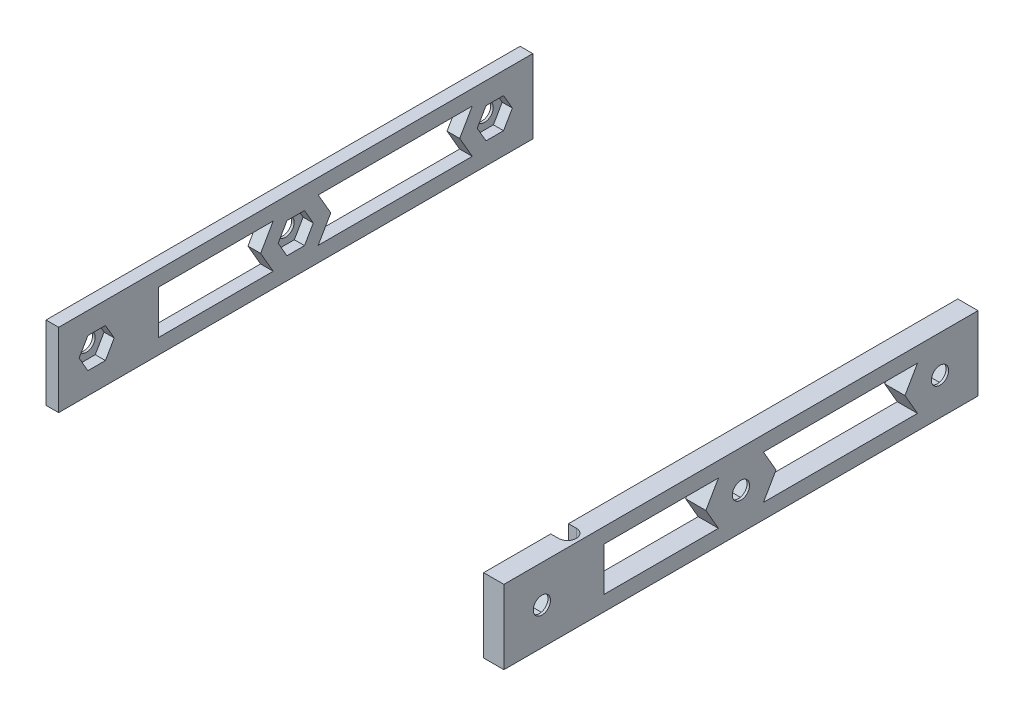
SolidWorks part; units mm, degrees
ref_plane "Front Plane" through (0, 0, 0) normal (0, 0, 1) x (1, 0, 0)
ref_plane "Top Plane" through (0, 0, 0) normal (0, 1, 0) x (1, 0, 0)
ref_plane "Right Plane" through (0, 0, 0) normal (1, 0, 0) x (0, 0, -1)
sketch "Sketch1" plane through (0, 0, 0) normal (0, 1, 0) x (1, 0, 0)
  line L1 (-45.2, -46.8) -> (45.2, -46.8)
  line L2 (-45.2, -46.8) -> (-45.2, 46.8)
  line L3 (-45.2, 46.8) -> (45.2, 46.8)
  line L4 (45.2, -46.8) -> (45.2, 46.8)
  line L5 (-45.2, -46.8) -> (45.2, 46.8) construction
  line L6 (-45.2, 46.8) -> (45.2, -46.8) construction
  line L7 (-45.2, -46.8) -> (-42.7, -46.8)
  line L8 (-45.2, -46.8) -> (-45.2, 46.8)
  line L9 (-45.2, 46.8) -> (-42.7, 46.8)
  line L10 (-42.7, -46.8) -> (-42.7, 46.8)
  line L11 (-45.2, -46.8) -> (-42.7, 46.8) construction
  line L12 (-45.2, 46.8) -> (-42.7, -46.8) construction
  line L13 (45.2, -46.8) -> (41.2, -46.8)
  line L14 (45.2, -46.8) -> (45.2, 46.8)
  line L15 (45.2, 46.8) -> (41.2, 46.8)
  line L16 (41.2, -46.8) -> (41.2, 46.8)
  line L17 (45.2, -46.8) -> (41.2, 46.8) construction
  line L18 (45.2, 46.8) -> (41.2, -46.8) construction
  point P0 (0, 0)
  point P6 (-43.95, 0)
  point P11 (43.2, 0)
  dimension "D1" = 93.6
  dimension "D2" = 90.4
  dimension "D3" = 2.5
  dimension "D4" = 4
extrude "Boss-Extrude1" add sketch "Sketch1" along normal blind 14.6 contours L1 L10 L3 L2 | L16 L1 L4 L3
sketch "Sketch4" plane through (0, 14.6, 0) normal (0, 1, 0) x (1, 0, 0)
  line L0 (41.2, -46.8) -> (45.2, -46.8) construction
  line L1 (45.2, -46.8) -> (45.2, 46.8) construction
  line L2 (42.75, -31.8) -> (42.75, -30.05)
  line L3 (42.75, -30.05) -> (41.2, -30.05)
  line L4 (41.2, -46.8) -> (41.2, 46.8) construction
  line L5 (42.75, -31.8) -> (42.75, -33.55)
  line L6 (42.75, -33.55) -> (41.2, -33.55)
  line L7 (41.2, -33.55) -> (41.2, -30.05)
  circle A0 centre (42.75, -31.8) radius 1.75
  line M2 (41.2, 46.8) -> (41.2, -46.8)
  dimension "D3" = 3.5
  dimension "D1" = 15
  dimension "D2" = 2.45
extrude "Cut-Extrude1" cut sketch "Sketch4" against normal through all contours L5 A0 L2 | L2 A0 L7 L5 | A0 L6 M2 | A0 L3 M2
hole_wizard "M3 Clearance Hole1" positions "Sketch6" profile "Sketch7" hole size "M3" standard "ANSI Metric" end condition through all
sketch "Sketch6" plane through (45.2, 0, 0) normal (1, 0, 0) x (0, 0, -1)
  line L0 (-46.8, 7.3) -> (46.8, 7.3)
  line L1 (-46.8, 14.6) -> (-46.8, 0) construction
  line L2 (46.8, 14.6) -> (46.8, 0) construction
  point P8 (-39.3, 7.3)
  point P10 (39.3, 7.3)
  point P12 (0, 7.3)
  dimension "D1" = 7.5
  dimension "D2" = 7.5
sketch "Sketch7" plane through (45.2, 7.3, 0) normal (0, 1, 0) x (0, 0, -1)
  line L0 (0, 0) -> (0, 90.4)
  line L1 (0, 90.4) -> (1.7, 90.4)
  line L2 (1.7, 90.4) -> (1.7, 0)
  line L5 (1.7, 0) -> (0, 0)
  line L11 (0, -6.35) -> (0, 107.95) construction
  dimension "Thru Hole Dia." = 3.4
  dimension "Thru Hole Depth" = 90.4
sketch "Sketch8" plane through (41.2, 0, 0) normal (-1, 0, 0) x (0, 0, 1)
  line L1 (-35.8359, 7.3) -> (-37.5679, 10.3)
  line L2 (-37.5679, 10.3) -> (-41.0321, 10.3)
  line L3 (-41.0321, 10.3) -> (-42.7641, 7.3)
  line L4 (-42.7641, 7.3) -> (-41.0321, 4.3)
  line L5 (-41.0321, 4.3) -> (-37.5679, 4.3)
  line L6 (-37.5679, 4.3) -> (-35.8359, 7.3)
  line L7 (3.4641, 7.3) -> (1.7321, 10.3)
  line L8 (1.7321, 10.3) -> (-1.7321, 10.3)
  line L9 (-1.7321, 10.3) -> (-3.4641, 7.3)
  line L10 (-3.4641, 7.3) -> (-1.7321, 4.3)
  line L11 (-1.7321, 4.3) -> (1.7321, 4.3)
  line L12 (1.7321, 4.3) -> (3.4641, 7.3)
  line L13 (42.7641, 7.3) -> (41.0321, 10.3)
  line L14 (41.0321, 10.3) -> (37.5679, 10.3)
  line L15 (37.5679, 10.3) -> (35.8359, 7.3)
  line L16 (35.8359, 7.3) -> (37.5679, 4.3)
  line L17 (37.5679, 4.3) -> (41.0321, 4.3)
  line L18 (41.0321, 4.3) -> (42.7641, 7.3)
  circle A0 centre (-39.3, 7.3) radius 3.4641 construction
  circle A1 centre (0, 7.3) radius 3.4641 construction
  circle A2 centre (39.3, 7.3) radius 3 construction
  dimension "D1" = 3
extrude "Cut-Extrude2" cut sketch "Sketch8" against normal blind 3.5
mirror "Mirror1" about plane through (0, 0, 0) normal (1, 0, 0) of "Cut-Extrude2"
sketch "Sketch10" [suppressed] plane through (0, 14.6, 0) normal (0, 1, 0) x (1, 0, 0)
  line L0 (42.75, -33.55) -> (41.2, -33.55) construction
  line L1 (41.2, -33.55) -> (41.2, -46.8) construction
  line L2 (41.2, -46.8) -> (45.2, -46.8) construction
  line L3 (45.2, -46.8) -> (45.2, 46.8) construction
  line L4 (45.2, 46.8) -> (41.2, 46.8) construction
  line L5 (41.2, 46.8) -> (41.2, -30.05) construction
  line L6 (41.2, -30.05) -> (42.75, -30.05) construction
  line L7 (-45.2, -46.8) -> (-42.7, -46.8) construction
  line L8 (-42.7, -46.8) -> (-42.7, 46.8) construction
  line L9 (-42.7, 46.8) -> (-45.2, 46.8) construction
  line L10 (-45.2, 46.8) -> (-45.2, -46.8) construction
  line L11 (42.75, -33.55) -> (41.2, -33.55)
  line L12 (41.2, -33.55) -> (41.2, -46.8)
  line L13 (41.2, -46.8) -> (45.2, -46.8)
  line L14 (45.2, -46.8) -> (45.2, 46.8)
  line L15 (45.2, 46.8) -> (41.2, 46.8)
  line L16 (41.2, 46.8) -> (41.2, -30.05)
  line L17 (41.2, -30.05) -> (42.75, -30.05)
  line L18 (-45.2, -46.8) -> (-42.7, -46.8)
  line L19 (-42.7, -46.8) -> (-42.7, 46.8)
  line L20 (-42.7, 46.8) -> (-45.2, 46.8)
  line L21 (-45.2, 46.8) -> (-45.2, -46.8)
  arc A0 (42.75, -33.55) -> (42.75, -30.05) centre (42.75, -31.8) ccw construction
  arc A1 (42.75, -33.55) -> (42.75, -30.05) centre (42.75, -31.8) ccw
extrude "Boss-Extrude2" [suppressed] add sketch "Sketch10" along normal blind 7.5
sketch "Sketch11" [suppressed] plane through (0, 0, 0) normal (0, -1, 0) x (1, 0, 0)
  line L0 (-42.7, 46.8) -> (-45.2, 46.8) construction
  line L1 (-45.2, 46.8) -> (-45.2, -46.8) construction
  line L2 (-45.2, -46.8) -> (-42.7, -46.8) construction
  line L3 (-42.7, -46.8) -> (-42.7, 46.8) construction
  line L4 (41.2, 33.55) -> (42.75, 33.55) construction
  line L5 (42.75, 30.05) -> (41.2, 30.05) construction
  line L6 (41.2, 30.05) -> (41.2, -46.8) construction
  line L7 (41.2, -46.8) -> (45.2, -46.8) construction
  line L8 (45.2, -46.8) -> (45.2, 46.8) construction
  line L9 (45.2, 46.8) -> (41.2, 46.8) construction
  line L10 (41.2, 46.8) -> (41.2, 33.55) construction
  line L11 (-42.7, 46.8) -> (-45.2, 46.8)
  line L12 (-45.2, 46.8) -> (-45.2, -46.8)
  line L13 (-45.2, -46.8) -> (-42.7, -46.8)
  line L14 (-42.7, -46.8) -> (-42.7, 46.8)
  line L15 (41.2, 33.55) -> (42.75, 33.55)
  line L16 (42.75, 30.05) -> (41.2, 30.05)
  line L17 (41.2, 30.05) -> (41.2, -46.8)
  line L18 (41.2, -46.8) -> (45.2, -46.8)
  line L19 (45.2, -46.8) -> (45.2, 46.8)
  line L20 (45.2, 46.8) -> (41.2, 46.8)
  line L21 (41.2, 46.8) -> (41.2, 33.55)
  arc A0 (42.75, 30.05) -> (42.75, 33.55) centre (42.75, 31.8) ccw construction
  arc A1 (42.75, 30.05) -> (42.75, 33.55) centre (42.75, 31.8) ccw
extrude "Boss-Extrude3" [suppressed] add sketch "Sketch11" along normal blind 7.5
sketch "Sketch12" [suppressed] plane through (41.2, 0, 0) normal (-1, 0, 0) x (0, 0, 1)
  line L0 (-32.3718, 7.3) -> (-35.8359, 1.3)
  line L1 (-35.8359, 1.3) -> (-42.7641, 1.3)
  line L2 (-42.7641, 1.3) -> (-46.2282, 7.3)
  line L3 (-46.2282, 7.3) -> (-42.7641, 13.3)
  line L4 (-42.7641, 13.3) -> (-35.8359, 13.3)
  line L5 (-35.8359, 13.3) -> (-32.3718, 7.3)
  line L7 (3.4641, 13.3) -> (6.9282, 7.3)
  line L8 (-35.8359, 7.3) -> (-37.5679, 4.3) construction
  line L9 (-37.5679, 4.3) -> (-41.0321, 4.3) construction
  line L10 (-41.0321, 4.3) -> (-42.7641, 7.3) construction
  line L11 (-42.7641, 7.3) -> (-41.0321, 10.3) construction
  line L12 (28.05, -5.5) -> (28.05, 20.1)
  line L13 (28.05, 20.1) -> (-44.8, 20.1)
  line L14 (-44.8, 20.1) -> (-44.8, -5.5)
  line L15 (-44.8, -5.5) -> (28.05, -5.5)
  line L16 (28.05, -5.5) -> (28.05, 20.1)
  line L17 (28.05, 20.1) -> (-44.8, 20.1)
  line L18 (-44.8, 20.1) -> (-44.8, -5.5)
  line L19 (-44.8, -5.5) -> (28.05, -5.5)
  line L20 (-41.0321, 10.3) -> (-37.5679, 10.3) construction
  line L21 (-37.5679, 10.3) -> (-35.8359, 7.3) construction
  line L22 (3.4641, 7.3) -> (1.7321, 4.3) construction
  line L23 (1.7321, 4.3) -> (-1.7321, 4.3) construction
  line L24 (-1.7321, 4.3) -> (-3.4641, 7.3) construction
  line L25 (-3.4641, 7.3) -> (-1.7321, 10.3) construction
  line L26 (-1.7321, 10.3) -> (1.7321, 10.3) construction
  line L27 (1.7321, 10.3) -> (3.4641, 7.3) construction
  line L28 (-35.8359, 7.3) -> (-37.5679, 4.3)
  line L29 (-37.5679, 4.3) -> (-41.0321, 4.3)
  line L30 (-41.0321, 4.3) -> (-42.7641, 7.3)
  line L31 (-42.7641, 7.3) -> (-41.0321, 10.3)
  line L32 (-41.0321, 10.3) -> (-37.5679, 10.3)
  line L33 (-37.5679, 10.3) -> (-35.8359, 7.3)
  line L34 (3.4641, 7.3) -> (1.7321, 4.3)
  line L35 (1.7321, 4.3) -> (-1.7321, 4.3)
  line L36 (-1.7321, 4.3) -> (-3.4641, 7.3)
  line L37 (-3.4641, 7.3) -> (-1.7321, 10.3)
  line L38 (-1.7321, 10.3) -> (1.7321, 10.3)
  line L39 (1.7321, 10.3) -> (3.4641, 7.3)
  line L40 (6.9282, 7.3) -> (3.4641, 1.3)
  line L41 (3.4641, 1.3) -> (-3.4641, 1.3)
  line L42 (-3.4641, 1.3) -> (-6.9282, 7.3)
  line L43 (-6.9282, 7.3) -> (-3.4641, 13.3)
  line L44 (-3.4641, 13.3) -> (3.4641, 13.3)
  line L45 (-35.8359, 13.3) -> (-35.8359, 20.1)
  line L46 (-35.8359, 1.3) -> (-35.8359, -5.5)
  line L47 (-3.4641, 1.3) -> (-3.4641, -5.5)
  line L48 (3.4641, 1.3) -> (3.4641, -5.5)
  line L49 (3.4641, 13.3) -> (3.4641, 20.1)
  line L50 (-3.4641, 13.3) -> (-3.4641, 20.1)
  dimension "D1" = 2
  dimension "D2" = 3
  dimension "D3" = 3
extrude "Cut-Extrude3" [suppressed] cut sketch "Sketch12" against normal through all both and the other way through all contours L43 L50 L17 L45 L5 L0 L46 L19 L47 L42 | L49 L7 L40 L48 L19 L16 L17
sketch "Sketch14" plane through (41.2, 0, 0) normal (-1, 0, 0) x (0, 0, 1)
  line L14 (27.05, 3) -> (27.05, 11.6)
  line L15 (-43.8, 3) -> (27.05, 3)
  line L16 (-43.8, 11.6) -> (-43.8, 3)
  line L17 (27.05, 11.6) -> (-43.8, 11.6)
  line L18 (27.05, 3) -> (27.05, 11.6)
  line L19 (-43.8, 3) -> (27.05, 3)
  line L20 (-43.8, 11.6) -> (-43.8, 3)
  line L21 (27.05, 11.6) -> (-43.8, 11.6)
  line L42 (-42.7641, 13.3) -> (-46.2282, 7.3)
  line L43 (-46.2282, 7.3) -> (-42.7641, 1.3)
  line L44 (-42.7641, 1.3) -> (-35.8359, 1.3)
  line L45 (-35.8359, 1.3) -> (-32.3718, 7.3)
  line L46 (-32.3718, 7.3) -> (-35.8359, 13.3)
  line L47 (-35.8359, 13.3) -> (-42.7641, 13.3)
  line L48 (-42.7641, 13.3) -> (-46.2282, 7.3)
  line L49 (-46.2282, 7.3) -> (-42.7641, 1.3)
  line L50 (-42.7641, 1.3) -> (-35.8359, 1.3)
  line L51 (-35.8359, 1.3) -> (-32.3718, 7.3)
  line L52 (-32.3718, 7.3) -> (-35.8359, 13.3)
  line L53 (-35.8359, 13.3) -> (-42.7641, 13.3)
  line L60 (-3.4641, 13.3) -> (-6.9282, 7.3)
  line L61 (3.4641, 13.3) -> (-3.4641, 13.3)
  line L62 (6.9282, 7.3) -> (3.4641, 13.3)
  line L63 (3.4641, 1.3) -> (6.9282, 7.3)
  line L64 (-3.4641, 1.3) -> (3.4641, 1.3)
  line L65 (-6.9282, 7.3) -> (-3.4641, 1.3)
  line L66 (-3.4641, 13.3) -> (-6.9282, 7.3)
  line L67 (3.4641, 13.3) -> (-3.4641, 13.3)
  line L68 (6.9282, 7.3) -> (3.4641, 13.3)
  line L69 (3.4641, 1.3) -> (6.9282, 7.3)
  line L70 (-3.4641, 1.3) -> (3.4641, 1.3)
  line L71 (-6.9282, 7.3) -> (-3.4641, 1.3)
  dimension "D1" = 3
  dimension "D2" = 3
  dimension "D3" = 3
extrude "Cut-Extrude4" cut sketch "Sketch14" against normal through all both and the other way through all contours L71 L66 L21 L52 L51 L19 | L69 L19 L18 L21 L68
